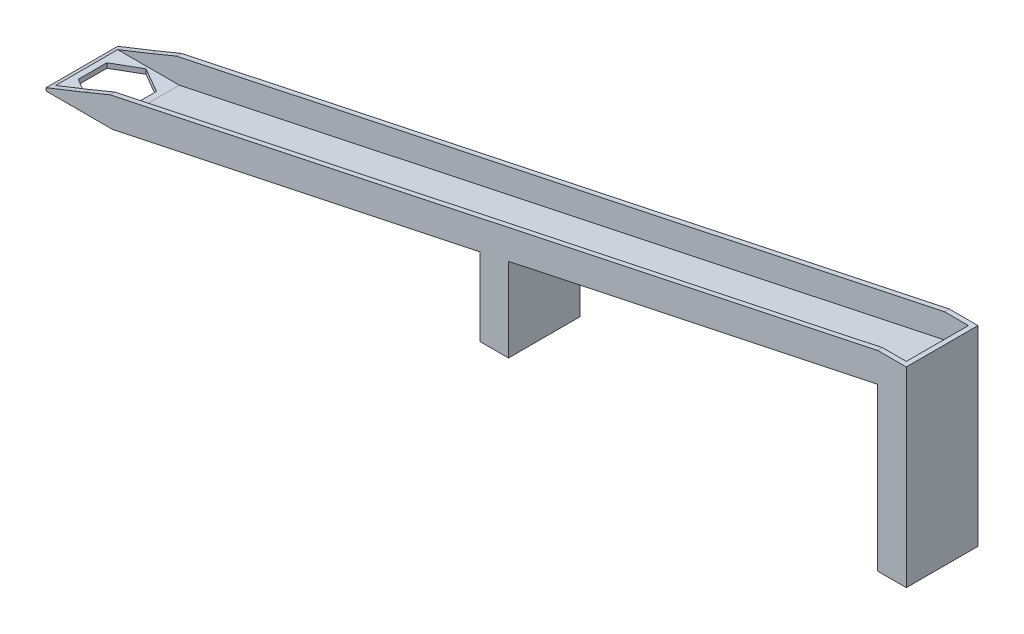
SolidWorks part; units mm, degrees
ref_plane "정면" through (0, 0, 0) normal (0, 0, 1) x (1, 0, 0)
ref_plane "윗면" through (0, 0, 0) normal (0, 1, 0) x (1, 0, 0)
ref_plane "우측면" through (0, 0, 0) normal (1, 0, 0) x (0, 0, -1)
sketch "Sketch2" plane through (0, 0, 0) normal (0, 0, 1) x (1, 0, 0)
  line L0 (0, 0) -> (70, 0)
  line L1 (70, 0) -> (870, 169.3353)
  line L8 (900, 169.3353) -> (900, 200)
  line L9 (900, 200) -> (870, 200)
  line L10 (870, 200) -> (66.8598, 30)
  line L11 (66.8598, 30) -> (0, 30)
  line L12 (0, 30) -> (0, 0)
  line L13 (870, 169.3353) -> (900, 169.3353)
  point P13 (0, 15)
  dimension "D1" = 70
  dimension "D2" = 30
  dimension "D3" = 30
  dimension "D6" = 30
  dimension "D7" = 900
extrude "Boss-Extrude2" add sketch "Sketch2" along normal blind 75
shell "Shell1" thickness 5
sketch "Sketch9" plane through (0, 5, 0) normal (0, 1, 0) x (1, 0, 0)
  line L1 (37.2102, -7.5818) -> (11.2294, -22.5818)
  line L2 (11.2294, -22.5818) -> (11.2294, -52.5818)
  line L3 (11.2294, -52.5818) -> (37.2102, -67.5818)
  line L4 (37.2102, -67.5818) -> (63.1909, -52.5818)
  line L5 (63.1909, -52.5818) -> (63.1909, -22.5818)
  line L6 (63.1909, -22.5818) -> (37.2102, -7.5818)
  circle A0 centre (37.2102, -37.5818) radius 25.9808 construction
  dimension "D1" = 60
extrude "Cut-Extrude2" cut sketch "Sketch9" against normal blind 60
sketch "Sketch11" plane through (0, 0, 75) normal (0, 0, 1) x (1, 0, 0)
  line L0 (66.8598, 30) -> (40.8957, 19.3052)
  line L1 (40.8957, 19.3052) -> (0, 3)
  line L2 (0, 3) -> (0, 30)
  line L3 (0, 30) -> (66.8598, 30)
extrude "Cut-Extrude4" cut sketch "Sketch11" against normal blind 90
sketch "Sketch12" plane through (0, 0, 75) normal (0, 0, 1) x (1, 0, 0)
  line L0 (900, 169.3353) -> (900, 0)
  line L1 (900, 0) -> (870, 0)
  line L2 (870, 0) -> (870, 169.3353)
  line L3 (870, 169.3353) -> (900, 169.3353)
  line L4 (453.8336, 81.2457) -> (453.8336, 0)
  line L5 (70, 0) -> (870, 169.3353) construction
  line L6 (453.8336, 0) -> (483.8336, 0)
  line L7 (483.8336, 0) -> (483.8336, 87.5958)
  line L8 (483.8336, 87.5958) -> (453.8336, 81.2457)
  dimension "D1" = 30
  dimension "D2" = 30
extrude "Boss-Extrude5" add sketch "Sketch12" against normal blind 75
